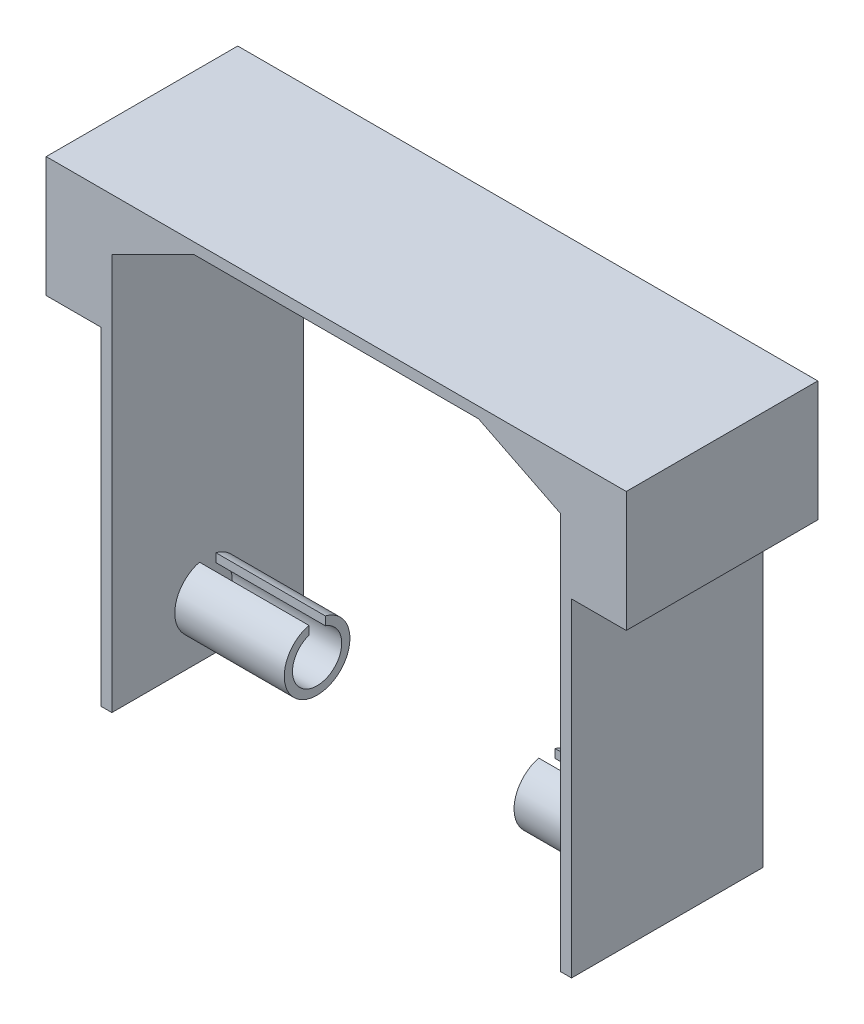
SolidWorks part; units mm, degrees
ref_plane "Alzado" through (0, 0, 0) normal (0, 0, 1) x (1, 0, 0)
ref_plane "Planta" through (0, 0, 0) normal (0, 1, 0) x (1, 0, 0)
ref_plane "Vista lateral" through (0, 0, 0) normal (1, 0, 0) x (0, 0, -1)
sketch "Croquis1" plane through (0, 0, 0) normal (1, 0, 0) x (0, 0, -1)
  line L2 (-3, 11.619) -> (-3, 8.4853)
  line L3 (3, 11.619) -> (3, 8.4853)
  arc A0 (-3, 8.4853) -> (3, 8.4853) centre (0, 0) ccw
  arc A1 (-3, 11.619) -> (3, 11.619) centre (0, 0) ccw
  point P9 (-1.5, 12)
  dimension "D1" = 18
  dimension "D2" = 24
extrude "Saliente-Extruir1" add sketch "Croquis1" along normal blind 40
sketch "Croquis2" plane through (0, 0, 0) normal (-1, 0, 0) x (0, 0, 1)
  line L1 (-35, 0) -> (-35, -20)
  line L2 (-35, -20) -> (35, -20)
  line L3 (35, -20) -> (35, 0)
  line L4 (-35, 0) -> (-35, 140)
  line L5 (-35, 140) -> (35, 140)
  line L6 (35, 140) -> (35, 0)
  point P3 (0, 0)
  dimension "D1" = 70
  dimension "D2" = 20
  dimension "D3" = 140
extrude "Saliente-Extruir2" add sketch "Croquis2" along normal blind 4
sketch "Croquis3" plane through (-4, 0, 0) normal (-1, 0, 0) x (0, 0, 1)
  line L0 (35, -20) -> (35, 140) construction
  line L1 (-35, 140) -> (35, 140)
  line L2 (-35, 140) -> (-35, 100)
  line L3 (-35, 100) -> (35, 100)
  line L4 (35, 140) -> (35, 100)
  dimension "D1" = 40
extrude "Saliente-Extruir3" add sketch "Croquis3" along normal blind 20
sketch "Croquis5" plane through (0, 0, 0) normal (0, 1, 0) x (1, 0, 0)
  line L1 (0, 35) -> (164, 35)
  line L2 (0, 35) -> (0, -35)
  line L3 (0, -35) -> (164, -35)
  line L4 (164, 35) -> (164, -35)
  dimension "D1" = 164
  dimension "D2" = 70
extrude "Saliente-Extruir4" add sketch "Croquis5" along normal blind 4 from offset 140 separate body
sketch "Croquis7" plane through (0, 0, 0) normal (1, 0, 0) x (0, 0, -1)
  line L1 (-35, 140) -> (35, 140)
  line L2 (-35, 140) -> (-35, -20)
  line L3 (-35, -20) -> (35, -20)
  line L4 (35, 140) -> (35, -20)
extrude "Saliente-Extruir5" add sketch "Croquis7" along normal blind 4 from offset 164 separate body
sketch "Croquis8" plane through (168, 0, 0) normal (1, 0, 0) x (0, 0, -1)
  line L0 (35, -20) -> (35, 140) construction
  line L1 (-35, 140) -> (35, 140)
  line L2 (-35, 140) -> (-35, 100)
  line L3 (-35, 100) -> (35, 100)
  line L4 (35, 140) -> (35, 100)
  dimension "D1" = 40
extrude "Saliente-Extruir6" add sketch "Croquis8" along normal blind 20
sketch "Croquis10" plane through (0, 140, 0) normal (0, 1, 0) x (1, 0, 0)
  line L1 (164, -35) -> (164, 35) construction
  line L2 (188, 35) -> (188, -35) construction
  line L3 (188, 25) -> (188, -25)
  line L5 (164, -25) -> (164, 25)
  line L8 (164, -25) -> (164, -35)
  line L9 (164, -35) -> (188, -35)
  line L10 (188, -35) -> (188, -25)
  line L11 (188, 25) -> (188, 35)
  line L12 (188, 35) -> (164, 35)
  line L13 (164, 35) -> (164, 25)
extrude "Saliente-Extruir12" add sketch "Croquis10" along normal blind 4
sketch "Croquis11" plane through (0, 140, 0) normal (0, 1, 0) x (1, 0, 0)
  line L1 (-24, 35) -> (0, 35)
  line L2 (-24, 35) -> (-24, -35)
  line L3 (-24, -35) -> (0, -35)
  line L4 (0, 35) -> (0, -35)
extrude "Saliente-Extruir13" add sketch "Croquis11" along normal blind 4
sketch "Croquis12" plane through (164, 0, 0) normal (-1, 0, 0) x (0, 0, 1)
  line L0 (0, -20) -> (0, 0)
  line L1 (35, -20) -> (-35, -20) construction
  line L4 (-3, 11.619) -> (-3, 8.4853)
  line L5 (3, 11.619) -> (3, 8.4853)
  arc A0 (-3, 8.4853) -> (3, 8.4853) centre (0, 0) ccw
  arc A1 (-3, 11.619) -> (3, 11.619) centre (0, 0) ccw
  point P12 (0, 12)
  dimension "D1" = 18
  dimension "D2" = 24
extrude "Saliente-Extruir14" add sketch "Croquis12" along normal blind 40 contours L0 A1 L5 A0 | L4 A1 L0 A0
sketch "Croquis13" plane through (0, 0, 0) normal (0, 0, 1) x (1, 0, 0)
  line L0 (164, 140) -> (134, 140)
  line L1 (0, 140) -> (164, 140) construction
  line L2 (164, 140) -> (164, 125)
  line L3 (164, 140) -> (164, -20) construction
  line L4 (134, 140) -> (164, 125)
  line L5 (0, 140) -> (30, 140)
  line L6 (0, 140) -> (0, 125)
  line L7 (0, -20) -> (0, 140) construction
  line L8 (0, 125) -> (30, 140)
  dimension "D1" = 30
  dimension "D2" = 15
  dimension "D3" = 30
extrude "Saliente-Extruir15" add sketch "Croquis13" along normal blind 10 from offset 25
sketch "Croquis14" plane through (0, 0, 0) normal (0, 0, 1) x (1, 0, 0)
  line L0 (164, 140) -> (134, 140)
  line L1 (134, 140) -> (164, 125)
  line L2 (164, -20) -> (164, 140) construction
  line L3 (164, 125) -> (164, 140) construction
  line L4 (164, 125) -> (164, 140)
  line L5 (0, 140) -> (30, 140)
  line L6 (30, 140) -> (0, 125)
  line L7 (0, 125) -> (0, 140)
extrude "Saliente-Extruir16" add sketch "Croquis14" against normal blind 10 from offset 25
